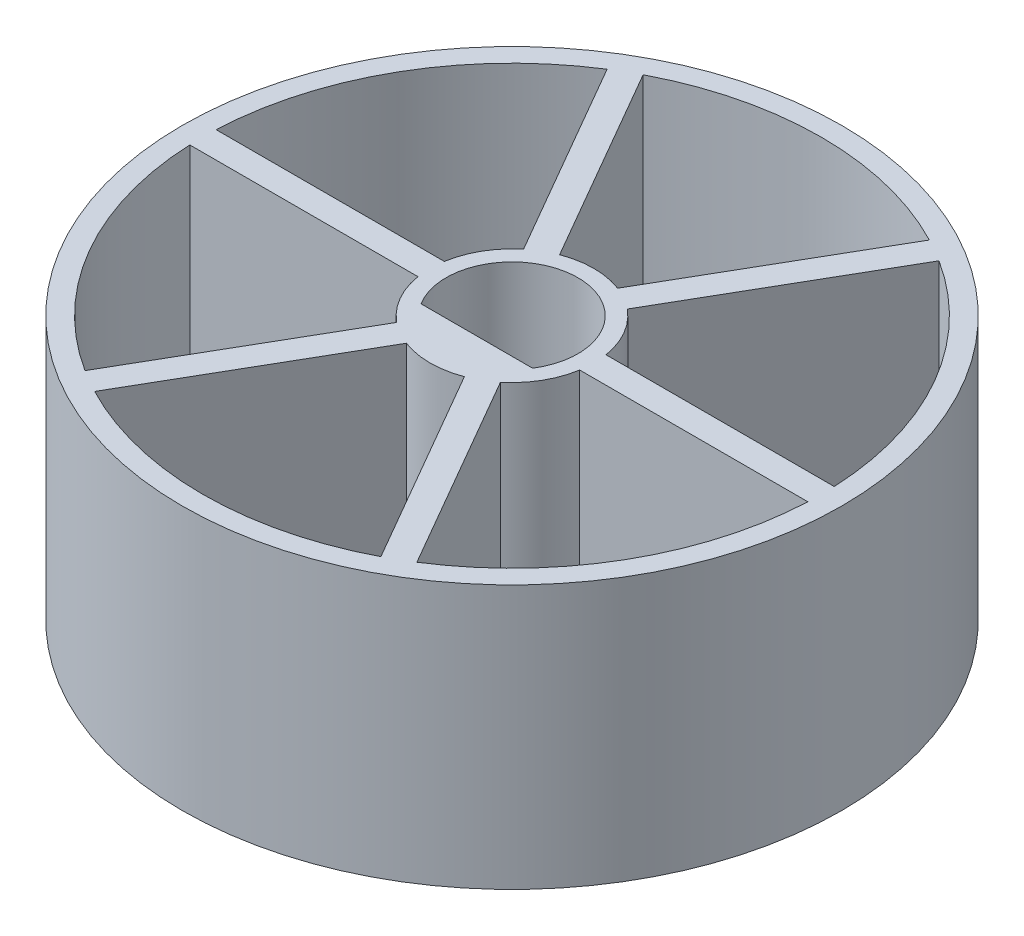
SolidWorks part; units mm, degrees
ref_plane "Ön Düzlem" through (0, 0, 0) normal (0, 0, 1) x (1, 0, 0)
ref_plane "Üst Düzlem" through (0, 0, 0) normal (0, 1, 0) x (1, 0, 0)
ref_plane "Sağ Düzlem" through (0, 0, 0) normal (1, 0, 0) x (0, 0, -1)
sketch "Çizim1" plane through (0, 0, 0) normal (0, 1, 0) x (1, 0, 0)
  line L1 (-6.3443, -4) -> (6.3443, -4)
  line L15 (-16.276, 31.1909) -> (-3.2992, 8.7143)
  line L16 (-18.8741, 29.6909) -> (-5.8972, 7.2143)
  line L17 (-35.1501, 1.5) -> (-9.1964, 1.5)
  line L19 (-35.1501, -1.5) -> (-9.1964, -1.5)
  line L21 (18.8741, 29.6909) -> (5.8972, 7.2143)
  line L22 (16.276, 31.1909) -> (3.2992, 8.7143)
  line L23 (35.1501, -1.5) -> (9.1964, -1.5)
  line L24 (35.1501, 1.5) -> (9.1964, 1.5)
  line L25 (16.276, -31.1909) -> (3.2992, -8.7143)
  line L26 (18.8741, -29.6909) -> (5.8972, -7.2143)
  line L27 (-18.8741, -29.6909) -> (-5.8972, -7.2143)
  line L28 (-16.276, -31.1909) -> (-3.2992, -8.7143)
  circle A0 centre (0, 0) radius 37.5
  arc A25 (-35.1508, -1.4824) -> (-18.8741, -29.6909) centre (0, 0) ccw
  arc A26 (-9.1964, -1.5) -> (-5.8972, -7.2143) centre (0, 0) ccw
  arc A27 (6.3443, -4) -> (-6.3443, -4) centre (0, 0) ccw
  arc A40 (-18.8741, 29.6909) -> (-35.1508, 1.4824) centre (0, 0) ccw
  arc A41 (-5.8972, 7.2143) -> (-9.1964, 1.5) centre (0, 0) ccw
  arc A42 (3.2992, 8.7143) -> (-3.2992, 8.7143) centre (0, 0) ccw
  arc A43 (9.1964, 1.5) -> (5.8972, 7.2143) centre (0, 0) ccw
  arc A44 (35.1501, 1.5) -> (18.8741, 29.6909) centre (0, 0) ccw
  arc A45 (16.276, 31.1909) -> (-16.276, 31.1909) centre (0, 0) ccw
  arc A46 (18.8741, -29.6909) -> (35.1501, -1.5) centre (0, 0) ccw
  arc A47 (5.8972, -7.2143) -> (9.1964, -1.5) centre (0, 0) ccw
  arc A48 (-3.2992, -8.7143) -> (3.2992, -8.7143) centre (0, 0) ccw
  arc A49 (-16.276, -31.1909) -> (16.276, -31.1909) centre (0, 0) ccw
  dimension "D1" = 75
  dimension "D2" = 6
extrude "Yükseklik-Ekstrüzyon1" add sketch "Çizim1" along normal blind 30
